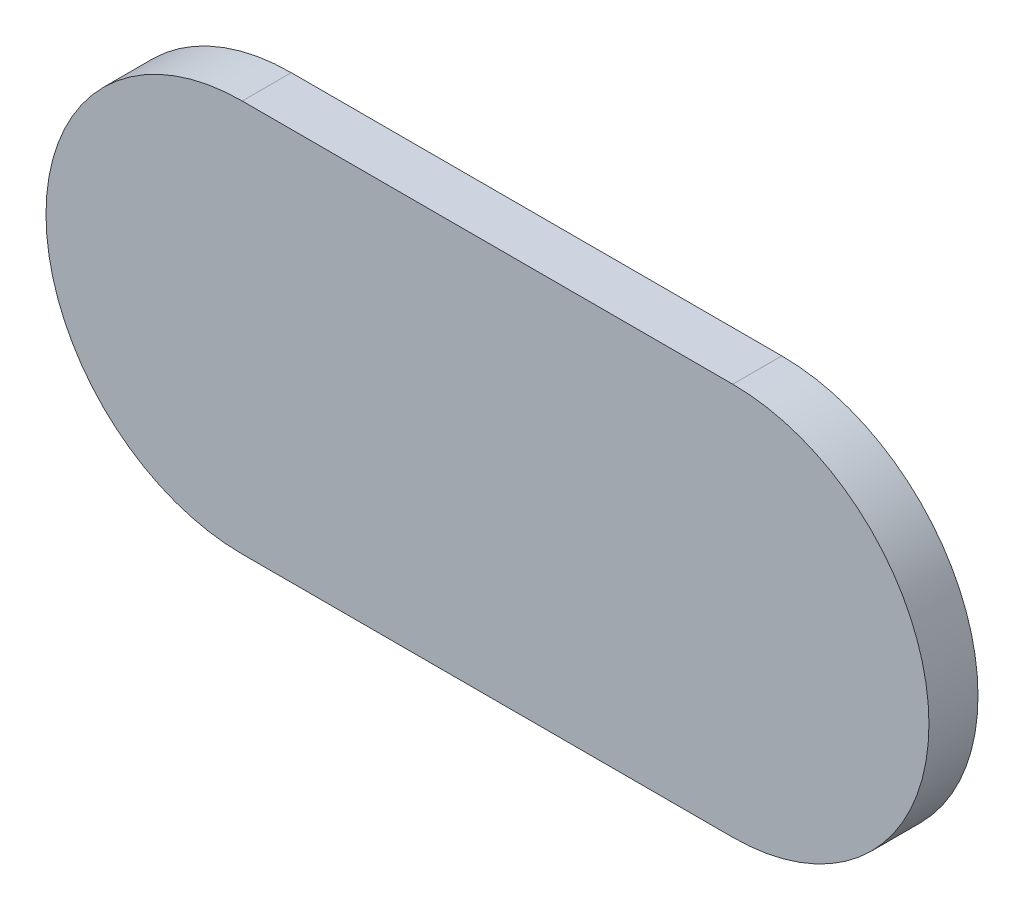
SolidWorks part; units mm, degrees
ref_plane "Front Plane" through (0, 0, 0) normal (0, 0, 1) x (1, 0, 0)
ref_plane "Top Plane" through (0, 0, 0) normal (0, 1, 0) x (1, 0, 0)
ref_plane "Right Plane" through (0, 0, 0) normal (1, 0, 0) x (0, 0, -1)
sketch "Sketch1" plane through (0, 0, 0) normal (0, 0, 1) x (1, 0, 0)
  line L0 (0, 0) -> (100, 0) construction
  line L1 (0, 40) -> (100, 40)
  line L2 (0, -40) -> (100, -40)
  arc A0 (0, 40) -> (0, -40) centre (0, 0) ccw
  arc A1 (100, -40) -> (100, 40) centre (100, 0) ccw
  point P3 (50, 0)
  dimension "D1" = 40
  dimension "D2" = 100
extrude "Boss-Extrude1" add sketch "Sketch1" along normal blind 10
